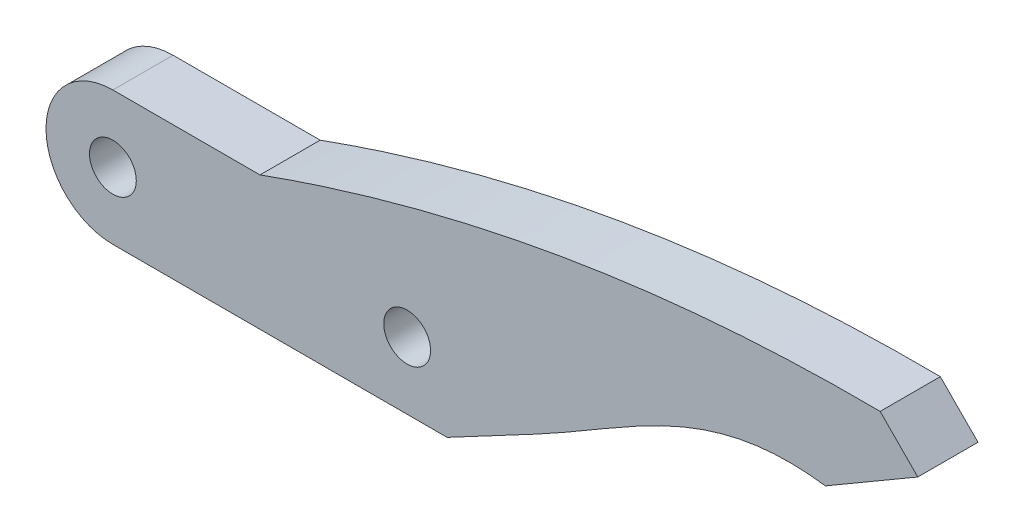
SolidWorks part; units mm, degrees
ref_plane "Front Plane" through (0, 0, 0) normal (0, 0, 1) x (1, 0, 0)
ref_plane "Top Plane" through (0, 0, 0) normal (0, 1, 0) x (1, 0, 0)
ref_plane "Right Plane" through (0, 0, 0) normal (1, 0, 0) x (0, 0, -1)
sketch "Sketch1" plane through (0, 0, 0) normal (0, 0, 1) x (1, 0, 0)
  line L0 (-11, 0) -> (11, 0) construction
  line L1 (0, 0) -> (0, 4.125) construction
  line L3 (-16, 5) -> (16, 5)
  line L4 (-16, 5) -> (-16, -5)
  line L5 (-16, -5) -> (16, -5)
  line L6 (16, 5) -> (16, -5)
  line L7 (-16, 5) -> (16, -5) construction
  line L8 (-16, -5) -> (16, 5) construction
  circle A0 centre (-11, 0) radius 1.75
  circle A2 centre (-11, 0) radius 5
  circle A3 centre (11, 0) radius 1.75
  circle A4 centre (11, 0) radius 5
  point P4 (0, 0)
  dimension "D2" = 3.5
  dimension "D3" = 10
  dimension "D1" = 22
extrude "Boss-Extrude1" add sketch "Sketch1" along normal blind 4.5 contours A2 A0 | A4 A3 | L5 A4 L3 A2
sketch "Sketch2" plane through (0, 0, 4.5) normal (0, 0, 1) x (1, 0, 0)
  line L0 (46.364, 12.87) -> (49.1808, 10.03)
  line L1 (49.1808, 10.03) -> (42.27, 6)
  line L2 (-11, -5) -> (11, -5) construction
  line L3 (11, 0) -> (11, -5) construction
  line L4 (20.61, -1.48) -> (13.99, -5)
  line L5 (13.99, -5) -> (11, -5)
  line L6 (-11, 5) -> (11, 5) construction
  line L8 (0, 5) -> (11, 5)
  arc A0 (11, -5) -> (11, 5) centre (11, 0) ccw construction
  arc A2 (11, -5) -> (11, 5) centre (11, 0) ccw
  spline S0 degree 3 poles (42.27, 6) (33.4578, 7.2137) (27.8016, 2.3439) (20.61, -1.48) knots 0 0 0 0 1 1 1 1
  spline S1 degree 2 poles (0, 5) (22.3875, 13.1151) (46.364, 12.87) knots 0 0 0 1 1 1
  dimension "D11" = 2.99
  dimension "D1" = 4
  dimension "D2" = 8
  dimension "D3" = 17.87
  dimension "D4" = 15.03
  dimension "D5" = 11
  dimension "D6" = 9.45
  dimension "D7" = 3.52
  dimension "D8" = 9.61
  dimension "D9" = 20.52
  dimension "D10" = 31.27
  dimension "D12" = 13.52
  dimension "D13" = 15.07
extrude "Boss-Extrude2" add sketch "Sketch2" against normal up to surface (4.5 mm away) up to face at (-9.25, 0, 0)
